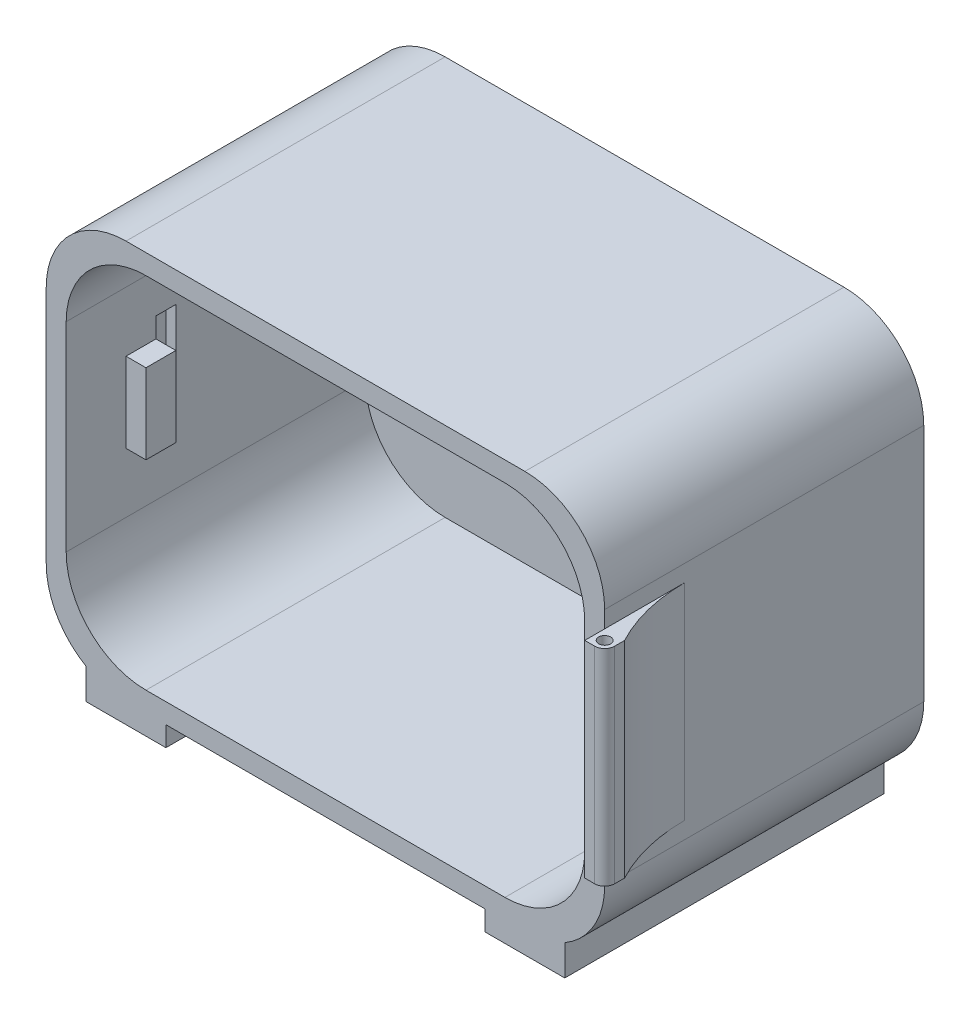
SolidWorks part; units mm, degrees
ref_plane "Front Plane" through (0, 0, 0) normal (0, 0, 1) x (1, 0, 0)
ref_plane "Top Plane" through (0, 0, 0) normal (0, 1, 0) x (1, 0, 0)
ref_plane "Right Plane" through (0, 0, 0) normal (1, 0, 0) x (0, 0, -1)
sketch "Sketch1" plane through (0, 0, 0) normal (0, 0, 1) x (1, 0, 0)
  line L0 (-82.55, 31.75) -> (-82.55, -31.75)
  line L1 (-63.5, 63.5) -> (63.5, 63.5)
  line L2 (-88.9, 38.1) -> (-88.9, -38.1)
  line L3 (-63.5, -63.5) -> (63.5, -63.5)
  line L4 (88.9, 38.1) -> (88.9, -38.1)
  line L5 (-88.9, 63.5) -> (88.9, -63.5) construction
  line L6 (-88.9, -63.5) -> (88.9, 63.5) construction
  line L7 (-57.15, -57.15) -> (57.15, -57.15)
  line L8 (82.55, 31.75) -> (82.55, -31.75)
  line L9 (-57.15, 57.15) -> (57.15, 57.15)
  line L10 (-88.9, 63.5) -> (88.9, 63.5) construction
  line L11 (88.9, 63.5) -> (88.9, -63.5) construction
  line L12 (82.55, 57.15) -> (82.55, -57.15) construction
  line L13 (-82.55, 57.15) -> (82.55, 57.15) construction
  line L14 (-82.55, -57.15) -> (82.55, -57.15) construction
  line L15 (-88.9, -63.5) -> (88.9, -63.5) construction
  line L16 (-82.55, 57.15) -> (-82.55, -57.15) construction
  line L17 (-88.9, 63.5) -> (-88.9, -63.5) construction
  arc A0 (63.5, 63.5) -> (88.9, 38.1) centre (63.5, 38.1) cw
  arc A1 (82.55, 31.75) -> (57.15, 57.15) centre (57.15, 31.75) ccw
  arc A2 (57.15, -57.15) -> (82.55, -31.75) centre (57.15, -31.75) ccw
  arc A3 (63.5, -63.5) -> (88.9, -38.1) centre (63.5, -38.1) ccw
  arc A4 (-82.55, -31.75) -> (-57.15, -57.15) centre (-57.15, -31.75) ccw
  arc A5 (-88.9, -38.1) -> (-63.5, -63.5) centre (-63.5, -38.1) ccw
  arc A6 (-63.5, 63.5) -> (-88.9, 38.1) centre (-63.5, 38.1) ccw
  arc A7 (-82.55, 31.75) -> (-57.15, 57.15) centre (-57.15, 31.75) cw
  point P0 (0, 0)
  dimension "D4" = 25.4
  dimension "D1" = 177.8
  dimension "D2" = 127
  dimension "D3" = 6.35
extrude "Boss-Extrude1" add sketch "Sketch1" against normal blind 95.25
sketch "Sketch2" plane through (0, 0, -95.25) normal (0, 0, -1) x (-1, 0, 0)
  line L0 (-63.5, 63.5) -> (63.5, 63.5)
  line L1 (-63.5, 63.5) -> (63.5, 63.5) construction
  line L2 (0, 63.5) -> (0, -63.5) construction
  line L3 (63.5, -63.5) -> (-63.5, -63.5) construction
  line L4 (63.5, -63.5) -> (-63.5, -63.5)
  line L5 (-88.9, -38.1) -> (-88.9, 38.1) construction
  line L6 (-88.9, -38.1) -> (-88.9, 38.1)
  line L7 (88.9, -38.1) -> (88.9, 38.1)
  arc A0 (-88.9, 38.1) -> (-63.5, 63.5) centre (-63.5, 38.1) cw
  arc A1 (-63.5, -63.5) -> (-88.9, -38.1) centre (-63.5, -38.1) cw
  arc A2 (-88.9, -38.1) -> (-63.5, -63.5) centre (-63.5, -38.1) ccw construction
  arc A3 (63.5, -63.5) -> (88.9, -38.1) centre (63.5, -38.1) ccw
  arc A4 (88.9, 38.1) -> (63.5, 63.5) centre (63.5, 38.1) ccw
extrude "Boss-Extrude2" add sketch "Sketch2" along normal blind 6.35
sketch "Sketch4" plane through (0, -63.5, 0) normal (0, -1, 0) x (1, 0, 0)
  line L0 (-76.2, 0) -> (-50.8, 0)
  line L2 (-76.2, 0) -> (-76.2, -101.6)
  line L3 (-88.9, -101.6) -> (-63.5, -101.6) construction
  line L4 (-76.2, -101.6) -> (-50.8, -101.6)
  line L5 (63.5, -101.6) -> (-63.5, -101.6) construction
  line L6 (-50.8, -101.6) -> (-50.8, 0)
  line L7 (0, 0) -> (0, -101.6) construction
  line L8 (-63.5, 0) -> (63.5, 0) construction
  line L9 (76.2, -101.6) -> (50.8, -101.6)
  line L10 (76.2, 0) -> (76.2, -101.6)
  line L11 (76.2, 0) -> (50.8, 0)
  line L12 (50.8, -101.6) -> (50.8, 0)
  point P4 (-63.5, 0)
  dimension "D1" = 25.4
extrude "Boss-Extrude3" add sketch "Sketch4" along normal blind 6.35 and the other way up to next
sketch "Sketch5" plane through (0, 0, 0) normal (0, 1, 0) x (1, 0, 0)
  line L0 (0, 0) -> (88.9, 0) construction
  line L1 (63.5, 0) -> (-63.5, 0) construction
  line L2 (92.075, 0) -> (95.25, 0) construction
  line L3 (88.9, 25.4) -> (88.9, 0)
  line L4 (92.075, 0) -> (92.075, -3.175) construction
  line L7 (95.25, -6.35) -> (88.9, -6.35)
  line L8 (95.25, -6.35) -> (95.25, 0)
  line L9 (95.25, 0) -> (92.075, 0)
  line L10 (88.9, -6.35) -> (88.9, 0)
  line L11 (95.25, -6.35) -> (88.9, 0) construction
  line L12 (95.25, 0) -> (88.9, -6.35) construction
  line L13 (88.9, -3.175) -> (95.25, -3.175) construction
  arc A3 (95.25, 0) -> (88.9, 25.4) centre (142.875, 25.4) cw
  circle A4 centre (92.075, -3.175) radius 1.905
  point P4 (93.6625, 0)
  dimension "D2" = 3.81
  dimension "D1" = 3.175
  dimension "D3" = 88.9
  dimension "D4" = 25.4
extrude "Boss-Extrude5" add sketch "Sketch5" along normal blind 32.766 and the other way blind 32.766
fillet "Fillet1" radius 3.175 1 edges at (95.25, 0, 6.35)
sketch "Sketch6" plane through (0, 32.766, 0) normal (0, 1, 0) x (1, 0, 0)
  line L0 (90.17, -3.175) -> (88.9, -3.175) construction
  line L1 (88.9, 0) -> (88.9, -6.35) construction
  line L2 (93.98, -3.175) -> (95.25, -3.175) construction
  circle A0 centre (92.075, -3.175) radius 1.905 construction
sketch "Sketch8" plane through (-82.55, 0, 0) normal (1, 0, 0) x (0, 0, -1)
  line L0 (0, -19.05) -> (28.575, -19.05) construction
  line L1 (0, 31.75) -> (0, -31.75) construction
  line L2 (28.575, -19.05) -> (34.925, -19.05)
  line L3 (34.925, -19.05) -> (34.925, 19.05)
  line L4 (34.925, 19.05) -> (28.575, 19.05)
  line L5 (28.575, 19.05) -> (28.575, -19.05)
  line L6 (95.25, -57.15) -> (0, -57.15) construction
  dimension "D1" = 28.575
  dimension "D2" = 6.35
  dimension "D3" = 38.1
  dimension "D4" = 38.1
extrude "Cut-Extrude1" cut sketch "Sketch8" against normal blind 3.175
sketch "Sketch10" plane through (-82.55, 0, 0) normal (1, 0, 0) x (0, 0, -1)
  line L0 (28.575, 0) -> (28.575, 12.7) construction
  line L1 (28.575, 19.05) -> (28.575, -19.05) construction
  line L3 (28.575, 12.7) -> (19.05, 12.7)
  line L4 (28.575, 12.7) -> (28.575, -12.7)
  line L5 (28.575, -12.7) -> (19.05, -12.7)
  line L6 (19.05, 12.7) -> (19.05, -12.7)
  point P7 (28.575, 0)
  dimension "D1" = 12.7
  dimension "D2" = 9.525
extrude "Boss-Extrude6" add sketch "Sketch10" along normal blind 6.35
sketch "Sketch11" plane through (0, 0, -101.6) normal (0, 0, -1) x (-1, 0, 0)
  line L0 (32.462, -188.0741) -> (352.462, -188.0741) construction
  line L1 (-8.558, 38.2776) -> (9.4147, 38.2776)
  line L2 (9.4147, 38.2776) -> (12.3761, 30.5166)
  line L3 (12.3761, 30.5166) -> (6.5554, 30.5166)
  line L4 (-8.558, 38.2776) -> (-26.541, -14.1457)
  line L5 (-26.541, -14.1457) -> (-20.9531, -14.1457)
  line L6 (-20.9531, -17.5278) -> (-27.8644, -17.5278)
  line L7 (-27.8644, -17.5278) -> (-30.0702, -24.7333)
  line L8 (-30.0702, -24.7333) -> (-9.6303, -24.7333)
  line L9 (-9.6303, -24.7333) -> (-7.4245, -17.5278)
  line L10 (-7.4245, -17.5278) -> (8.4569, -17.5278)
  line L11 (8.4569, -17.5278) -> (10.5156, -24.7333)
  line L12 (10.5156, -24.7333) -> (12.3761, -24.7333)
  line L13 (12.3761, -24.7333) -> (12.3761, -18.8513)
  line L14 (16.1034, -18.8513) -> (16.1034, -24.7333)
  line L15 (16.1034, -24.7333) -> (21.2502, -24.7333)
  line L16 (21.2502, -24.7333) -> (21.2502, -18.8513)
  line L17 (24.3382, -18.8513) -> (24.3382, -24.7333)
  line L18 (24.3382, -24.7333) -> (31.2496, -24.7333)
  line L19 (31.2496, -24.7333) -> (13.3095, 27.1753)
  line L20 (13.3095, 27.1753) -> (6.5554, 27.1753)
  line L21 (0.7548, 15.0295) -> (-4.8523, -6.6891)
  line L22 (-4.8523, -6.6891) -> (6.0184, -6.6891)
  line L23 (6.0184, -6.6891) -> (0.7548, 15.0295)
  arc A0 (6.5554, 30.5166) -> (6.5554, 27.1753) centre (2.9252, 28.8459) ccw
  arc A1 (12.3761, -18.8513) -> (16.1034, -18.8513) centre (14.2398, -15.2135) cw
  arc A2 (-20.9531, -14.1457) -> (-20.9531, -17.5278) centre (-17.0513, -15.8368) cw
  arc A3 (21.2502, -18.8513) -> (24.3382, -18.8513) centre (22.7942, -15.1977) cw
  circle A4 centre (2.9252, 28.8459) radius 1.6706
  circle A5 centre (-17.0513, -15.8368) radius 2.045
  circle A6 centre (14.2398, -15.2135) radius 2.3144
  circle A7 centre (22.7942, -15.1977) radius 1.5563
  circle A8 centre (0, 3.175) radius 44.8241
  point P39 (0.8064, 15.13)
  point P41 (-4.8655, -6.7402)
  point P42 (6.0184, -6.6891)
  point P43 (0, 15.1186)
  point P44 (0.7548, 15.0295)
  point P45 (0, 0)
  point P46 (0, 2.7081)
  dimension "D1" = 3.175
extrude "Cut-Extrude4" cut sketch "Sketch11" against normal blind 1.5875 contours A8 | L22 L23 L21 | A3 L17 L18 L19 L20 A0 L3 L2 L1 L4 L5 A2 L6 L7 L8 L9 L10 L11 L12 L13 A1 L14 L15 L16
sketch "Sketch12" plane through (0, 0, -101.6) normal (0, 0, -1) x (-1, 0, 0)
  line L0 (0, 0) -> (0, -57.15) construction
  line L1 (63.5, -57.15) -> (-63.5, -57.15) construction
  text T0 "amp-lab.org" font "Century Gothic" height in points 48
  point P6 (0, -57.15)
  dimension "D1" = 57.15
  dimension "D2" = 127
extrude "Cut-Extrude5" cut sketch "Sketch12" against normal blind 1.5875
